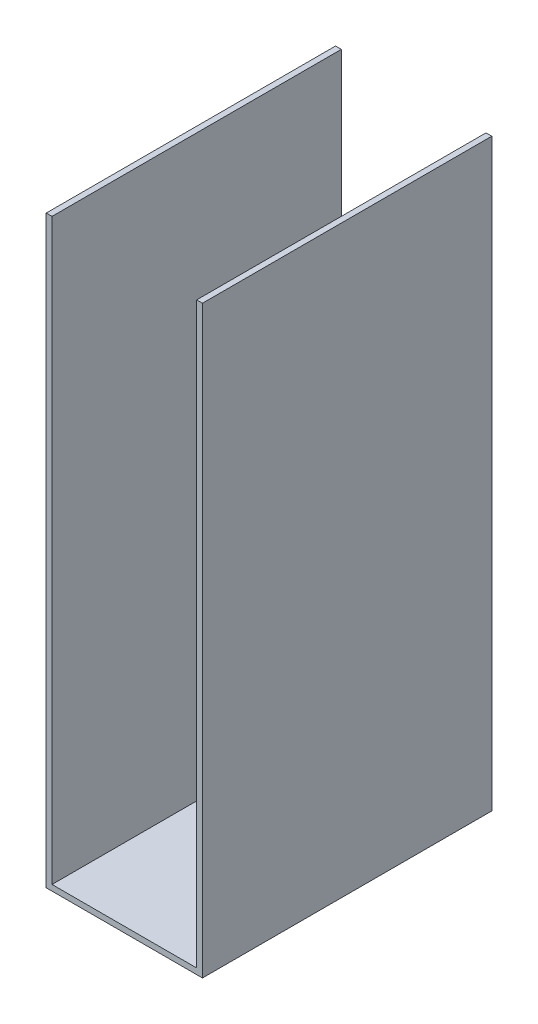
SolidWorks part; units mm, degrees
ref_plane "Front Plane" through (0, 0, 0) normal (0, 0, 1) x (1, 0, 0)
ref_plane "Top Plane" through (0, 0, 0) normal (0, 1, 0) x (1, 0, 0)
ref_plane "Right Plane" through (0, 0, 0) normal (1, 0, 0) x (0, 0, -1)
sketch "Sketch2" plane through (0, 0, 0) normal (0, 0, 1) x (1, 0, 0)
  line L0 (0, 0) -> (0, -20000)
  line L1 (0, -20000) -> (5000, -20000)
  line L2 (5000, -20000) -> (5000, 0)
  line L3 (-200, 0) -> (-200, -20200)
  line L4 (-200, -20200) -> (5200, -20200)
  line L5 (5200, -20200) -> (5200, 0)
  line L6 (-200, 0) -> (0, 0)
  line L7 (5000, 0) -> (5200, 0)
extrude "Boss-Extrude1" add sketch "Sketch2" along normal blind 10000
